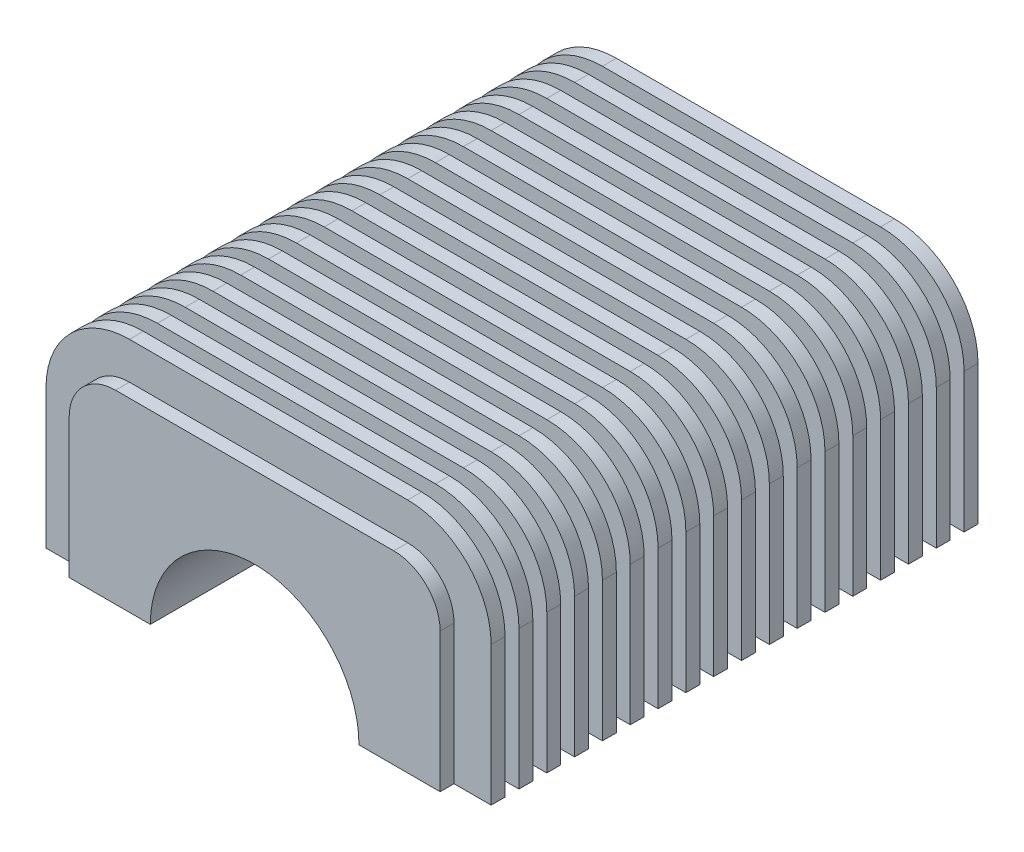
SolidWorks part; units mm, degrees
ref_plane "Płaszczyzna przednia" through (0, 0, 0) normal (0, 0, 1) x (1, 0, 0)
ref_plane "Płaszczyzna górna" through (0, 0, 0) normal (0, 1, 0) x (1, 0, 0)
ref_plane "Płaszczyzna prawa" through (0, 0, 0) normal (1, 0, 0) x (0, 0, -1)
sketch "Szkic1" plane through (0, 0, 0) normal (0, 0, 1) x (1, 0, 0)
  line L0 (-22.5, 0) -> (22.5, 0) construction
  line L2 (0, 0) -> (40, 40) construction
  line L3 (0, 0) -> (-40, 40) construction
  line L4 (-40, 40) -> (-40, 0)
  line L5 (-40, 40) -> (40, 40)
  line L6 (40, 40) -> (40, 0)
  line L7 (40, 0) -> (22.5, 0)
  line L8 (-40, 0) -> (-22.5, 0)
  arc A0 (-22.5, 0) -> (22.5, 0) centre (0, 0) cw
  dimension "D3" = 22.5
  dimension "D1" = 80
  dimension "D2" = 40
extrude "Dodanie-wyciągnięcie1" add sketch "Szkic1" along normal blind 108 contours L5 L6 L7 A0 L8 L4
fillet "Zaokrąglenie1" radius 10 2 edges at (-40, 40, 54) (40, 40, 54)
sketch "Szkic3" plane through (0, 0, 0) normal (0, 0, -1) x (-1, 0, 0)
  line L5 (48, 0) -> (40, 0)
  line L6 (-48, 0) -> (-40, 0)
  line L13 (-48, 0) -> (-48, 30)
  line L14 (48, 30) -> (48, 0)
  line L15 (-30, 48) -> (30, 48)
  line L16 (-48, 0) -> (-48, 30)
  line L17 (48, 30) -> (48, 0)
  line L18 (-30, 48) -> (30, 48)
  line L21 (40, 0) -> (40, 30)
  line L22 (30, 40) -> (-30, 40)
  line L23 (-40, 30) -> (-40, 0)
  line L24 (-40, 0) -> (-22.5, 0)
  line L25 (22.5, 0) -> (40, 0)
  line L29 (-40, 0) -> (-22.5, 0)
  line L30 (22.5, 0) -> (40, 0)
  arc A7 (-30, 48) -> (-48, 30) centre (-30, 30) ccw
  arc A8 (48, 30) -> (30, 48) centre (30, 30) ccw
  arc A9 (-30, 48) -> (-48, 30) centre (-30, 30) ccw
  arc A10 (48, 30) -> (30, 48) centre (30, 30) ccw
  arc A12 (40, 30) -> (30, 40) centre (30, 30) ccw
  arc A13 (-30, 40) -> (-40, 30) centre (-30, 30) ccw
  arc A14 (22.5, 0) -> (-22.5, 0) centre (0, 0) ccw
  arc A17 (22.5, 0) -> (-22.5, 0) centre (0, 0) ccw
  dimension "D1" = 8
  dimension "D2" = 0
extrude "Dodanie-wyciągnięcie2" add sketch "Szkic3" against normal blind 3 contours L18 A10 L17 L5 L30 A17 L29 L6 L16 A9
pattern_linear "Szyk liniowy1" count 18 spacing 6 along (0, 0, 1) of "Dodanie-wyciągnięcie2"
